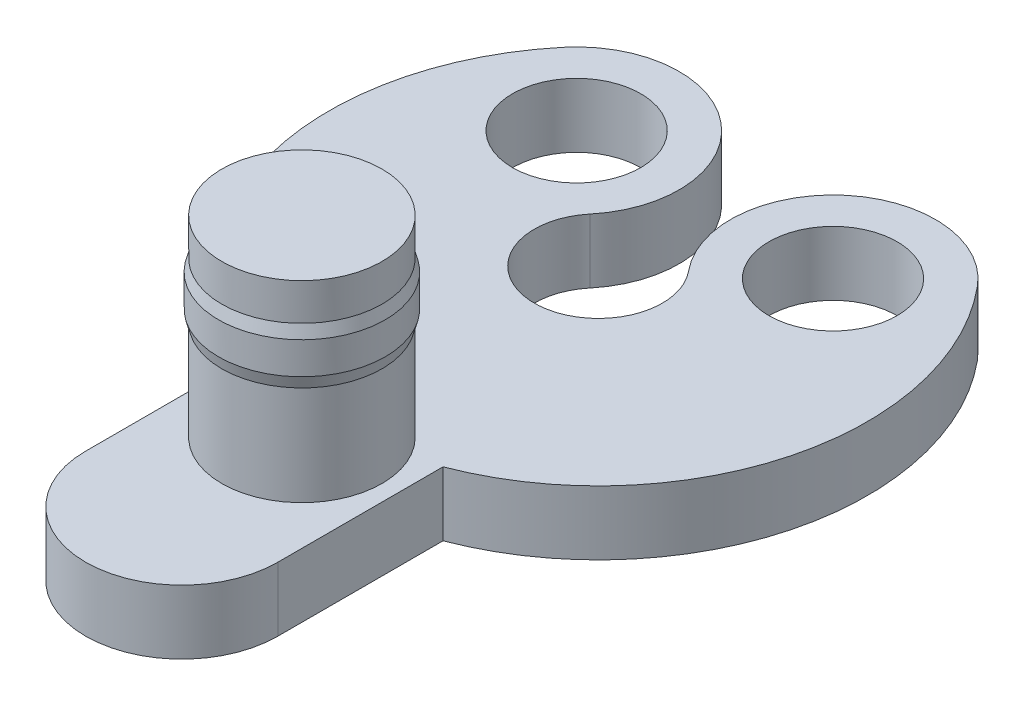
SolidWorks part; units mm, degrees
ref_plane "前视基准面" through (0, 0, 0) normal (0, 0, 1) x (1, 0, 0)
ref_plane "上视基准面" through (0, 0, 0) normal (0, 1, 0) x (1, 0, 0)
ref_plane "右视基准面" through (0, 0, 0) normal (1, 0, 0) x (0, 0, -1)
other "Configuration Table"
sketch "草图1" plane through (0, 0, 0) normal (0, 1, 0) x (1, 0, 0)
  line L0 (0, -6) -> (0, -13) construction
  line L1 (3, -7.846) -> (3, -13)
  line L2 (0, 0) -> (0, 8.7655) construction
  line L5 (-3, -7.846) -> (-3, -13)
  arc A0 (-6.4615, 5.3674) -> (-3, -7.846) centre (0, 0) ccw
  arc A1 (-1.5385, 1.2779) -> (1.5385, 1.2779) centre (0, 0) ccw
  circle A2 centre (-4, 3.3226) radius 2
  arc A3 (-6.4615, 5.3674) -> (-1.5385, 1.2779) centre (-4, 3.3226) cw
  circle A4 centre (4, 3.3226) radius 2
  arc A5 (6.4615, 5.3674) -> (1.5385, 1.2779) centre (4, 3.3226) ccw
  arc A7 (-3, -13) -> (3, -13) centre (0, -13) ccw
  arc A10 (3, -7.846) -> (6.4615, 5.3674) centre (0, 0) ccw
  point P8 (-4, 3.3226)
  point P15 (-4, 3.3226)
  dimension "D1" = 2
  dimension "D2" = 4
  dimension "D3" = 4
  dimension "D5" = 13
  dimension "D6" = 8.4
  dimension "D7" = 3
  dimension "D4" = 5.2
  dimension "D8" = 7
  dimension "D9" = 6
  dimension "D10" = 8.7655
extrude "凸台-拉伸1" add sketch "草图1" along normal blind 2
sketch "草图2" plane through (0, 0, 0) normal (0, -1, 0) x (1, 0, 0)
  circle A0 centre (0, 9.25) radius 2.5
  arc A1 (1.5385, -1.2779) -> (-1.5385, -1.2779) centre (0, 0) ccw construction
  dimension "D1" = 5
  dimension "D2" = 9.25
extrude "凸台-拉伸2" add sketch "草图2" against normal blind 8
sketch "草图3" plane through (3, 0, 0) normal (1, 0, 0) x (0, 0, -1)
  line L0 (-7.846, 2) -> (-13, 2) construction
  line L1 (-11.75, 8) -> (-11.75, 2) construction
  circle A0 centre (-12.4952, 4.9496) radius 0.5025
  dimension "D1" = 2.9496
  dimension "D2" = 0.7452
  dimension "D3" = 1.0049
sketch "草图4" plane through (0, 0, 0) normal (1, 0, 0) x (0, 0, -1)
  line L0 (-9.25, 8) -> (-9.25, 0.8785) construction
  line L1 (-6.75, 8) -> (-11.75, 8) construction
  line L2 (-9.25, 5.6884) -> (-6.75, 5.6884)
  line L3 (-6.75, 2) -> (-6.75, 8) construction
  line L4 (-6.75, 5.6884) -> (-11.3694, 5.3028)
  line L5 (-11.3694, 5.3028) -> (-11.3694, 4.444)
  line L6 (-11.3694, 4.444) -> (-6.75, 4.1779)
  line L7 (-6.75, 4.1779) -> (-9.25, 4.1779)
  line L8 (-9.25, 4.1779) -> (-9.25, 5.6884)
  line L9 (-11.75, 8) -> (-11.75, 2) construction
  line L10 (-7.846, 2) -> (-13, 2) construction
  dimension "D1" = 0.8588
  dimension "D2" = 0.3806
  dimension "D3" = 1.5105
  dimension "D4" = 7.1215
  dimension "D5" = 3.6884
  dimension "D6" = 0.3857
sketch "草图5" plane through (0, 8, 0) normal (0, 1, 0) x (1, 0, 0)
  line L0 (-0.058, -11.75) -> (0, -11.75)
  circle A0 centre (0, -9.25) radius 2.5 construction
  dimension "D1" = 0.058
  dimension "D2" = 11.75
sketch "草图6" plane through (0, 8, 0) normal (0, 1, 0) x (1, 0, 0)
  line L0 (0, -12.4564) -> (0, -15.9406) construction
  line L1 (3, -7.846) -> (3, -13) construction
  dimension "D1" = 3
  dimension "D2" = 3.4842
ref_plane "基准面1" through (0, 0, 11.75) normal (0, 0, 1) x (1, 0, 0)
sketch "草图7" plane through (0, 0, 11.4985) normal (-1, 0, 0) x (0, 0, 1)
  line L0 (-4.7485, 2) -> (0.2515, 2) construction
  line L1 (-2.2485, 2) -> (-2.2485, 7.7035) construction
  line L3 (-2.2485, 5.1) -> (0.2515, 5.1)
  line L7 (0.2515, 5.1) -> (0.3515, 5.4732)
  line L10 (0.3515, 5.4732) -> (0.3515, 6.4732)
  line L12 (0.3515, 6.4732) -> (0.2515, 6.8464)
  line L13 (0.2515, 2) -> (0.2515, 8) construction
  line L14 (0.2515, 6.8464) -> (-2.2485, 6.8464)
  line L15 (-2.2485, 6.8464) -> (-2.2485, 5.1)
  point P2 (-2.2485, 2)
  dimension "D1" = 3.1
  dimension "D2" = 105
  dimension "D3" = 105
  dimension "D4" = 2.6
  dimension "D5" = 1
revolve "旋转3" add sketch "草图7" angle 360 about L1
